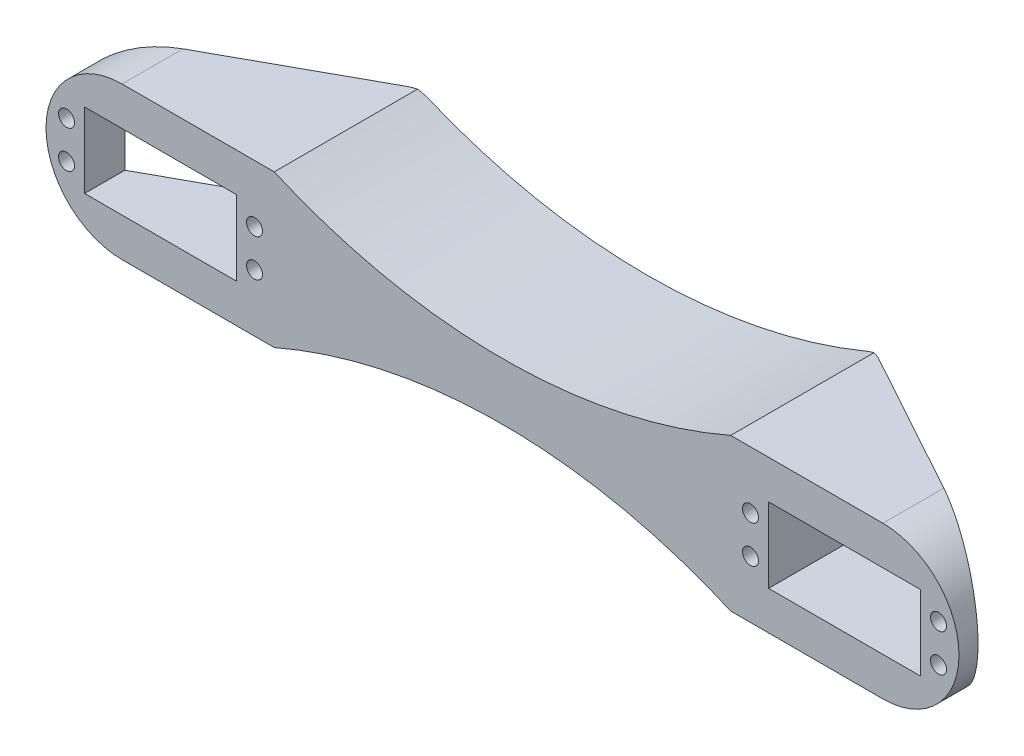
SolidWorks part; units mm, degrees
ref_plane "Front Plane" through (0, 0, 0) normal (0, 0, 1) x (1, 0, 0)
ref_plane "Top Plane" through (0, 0, 0) normal (0, 1, 0) x (1, 0, 0)
ref_plane "Right Plane" through (0, 0, 0) normal (1, 0, 0) x (0, 0, -1)
sketch "Sketch1" plane through (0, 0, 0) normal (0, 0, 1) x (1, 0, 0)
  line L0 (-79.0738, 18.5935) -> (120.9262, 18.5935) construction
  line L1 (-79.0738, 38.5935) -> (120.9262, 38.5935)
  line L2 (-79.0738, -1.4065) -> (120.9262, -1.4065)
  arc A0 (-79.0738, 38.5935) -> (-79.0738, -1.4065) centre (-79.0738, 18.5935) ccw
  arc A1 (120.9262, -1.4065) -> (120.9262, 38.5935) centre (120.9262, 18.5935) ccw
  circle A2 centre (-79.0738, 18.5935) radius 2.7394
  circle A3 centre (120.9262, 18.5935) radius 2.7394
  point P2 (20.9262, 18.5935)
  dimension "D1" = 200
  dimension "D2" = 20
extrude "Boss-Extrude1" add sketch "Sketch1" along normal blind 60
sketch "Sketch16" plane through (0, 0, 60) normal (0, 0, 1) x (1, 0, 0)
  line L0 (-88.9238, 28.4435) -> (-49.0238, 28.4435)
  line L1 (-88.6238, 28.4435) -> (-94.9738, 28.4435) construction
  line L2 (-42.9738, 28.4435) -> (-49.3238, 28.4435) construction
  line L3 (-49.0238, 28.4435) -> (-49.0238, 8.7435)
  line L4 (-49.3238, 8.7435) -> (-42.9738, 8.7435) construction
  line L5 (-49.0238, 8.7435) -> (-88.9238, 8.7435)
  line L6 (-94.9738, 8.7435) -> (-88.6238, 8.7435) construction
  line L7 (-88.9238, 8.7435) -> (-88.9238, 28.4435)
  circle A0 centre (-93.6849, 23.5185) radius 2.1
  circle A1 centre (-93.6849, 13.6685) radius 2.1
  circle A2 centre (-44.2626, 23.5185) radius 2.1
  circle A3 centre (-44.2626, 13.6685) radius 2.1
sketch "Sketch17" plane through (0, 0, 60) normal (0, 0, 1) x (1, 0, 0)
  line L0 (90.8762, 28.4435) -> (130.7762, 28.4435)
  line L1 (91.1762, 28.4435) -> (84.8262, 28.4435) construction
  line L2 (136.8262, 28.4435) -> (130.4762, 28.4435) construction
  line L3 (130.7762, 28.4435) -> (130.7762, 8.7435)
  line L4 (130.4762, 8.7435) -> (136.8262, 8.7435) construction
  line L5 (130.7762, 8.7435) -> (90.8762, 8.7435)
  line L6 (84.8262, 8.7435) -> (91.1762, 8.7435) construction
  line L7 (90.8762, 8.7435) -> (90.8762, 28.4435)
  circle A0 centre (86.1151, 23.5185) radius 2.1
  circle A1 centre (86.1151, 13.6685) radius 2.1
  circle A2 centre (135.5374, 23.5185) radius 2.1
  circle A3 centre (135.5374, 13.6685) radius 2.1
extrude "Cut-Extrude10" cut sketch "Sketch17" against normal through all
sketch "Sketch18" plane through (0, -1.4065, 0) normal (0, -1, 0) x (-1, 0, 0)
  line L1 (-140.9262, 0) -> (-140.9262, -60) construction
  line L2 (-140.9262, -55) -> (-140.9262, 0)
  line L5 (99.0738, -60) -> (99.0738, 0) construction
  line L6 (99.0738, -55) -> (99.0738, 0)
  line L8 (-140.9262, 0) -> (-40.9262, 0)
  line L9 (79.0738, 0) -> (-120.9262, 0) construction
  line L10 (99.0738, 0) -> (-0.9262, 0)
  line L11 (-40.9262, 0) -> (-140.9262, -55)
  line L12 (-0.9262, 0) -> (99.0738, -55)
  dimension "D1" = 55
  dimension "D2" = 55
  dimension "D3" = 100
  dimension "D4" = 100
  dimension "D5" = 114.1271
  dimension "D6" = 114.1271
extrude "Cut-Extrude11" cut sketch "Sketch18" against normal through all
sketch "Sketch19" plane through (0, -1.4065, 0) normal (0, -1, 0) x (-1, 0, 0)
  line L1 (-120.9262, -44) -> (-40.9262, 0) construction
  line L3 (42.1626, 0) -> (-80.9262, 0)
  line L4 (-80.9262, 0) -> (-80.9262, -22)
  line L5 (42.1626, 0) -> (42.1626, -22)
  line L6 (42.1626, -22) -> (-80.9262, -22)
extrude "Cut-Extrude12" cut sketch "Sketch19" against normal through all
sketch "Sketch22" plane through (0, 0, 22) normal (0, 0, -1) x (-1, 0, 0)
  line L0 (-80.9262, 38.5935) -> (39.0738, 38.5935)
  line L1 (-80.9262, -1.4065) -> (39.0738, -1.4065)
  arc A0 (-80.9262, 38.5935) -> (39.0738, 38.5935) centre (-20.9262, 176.0708) ccw
  arc A1 (-80.9262, -1.4065) -> (39.0738, -1.4065) centre (-20.9262, -138.8838) cw
extrude "Cut-Extrude14" cut sketch "Sketch22" against normal through all
fillet "Fillet3" radius 10 1 edges at (80.9262, 18.5935, 22)
fillet "Fillet4" radius 10 1 edges at (-39.0738, 18.5935, 22)
extrude "Cut-Extrude15" cut sketch "Sketch16" against normal blind 40
